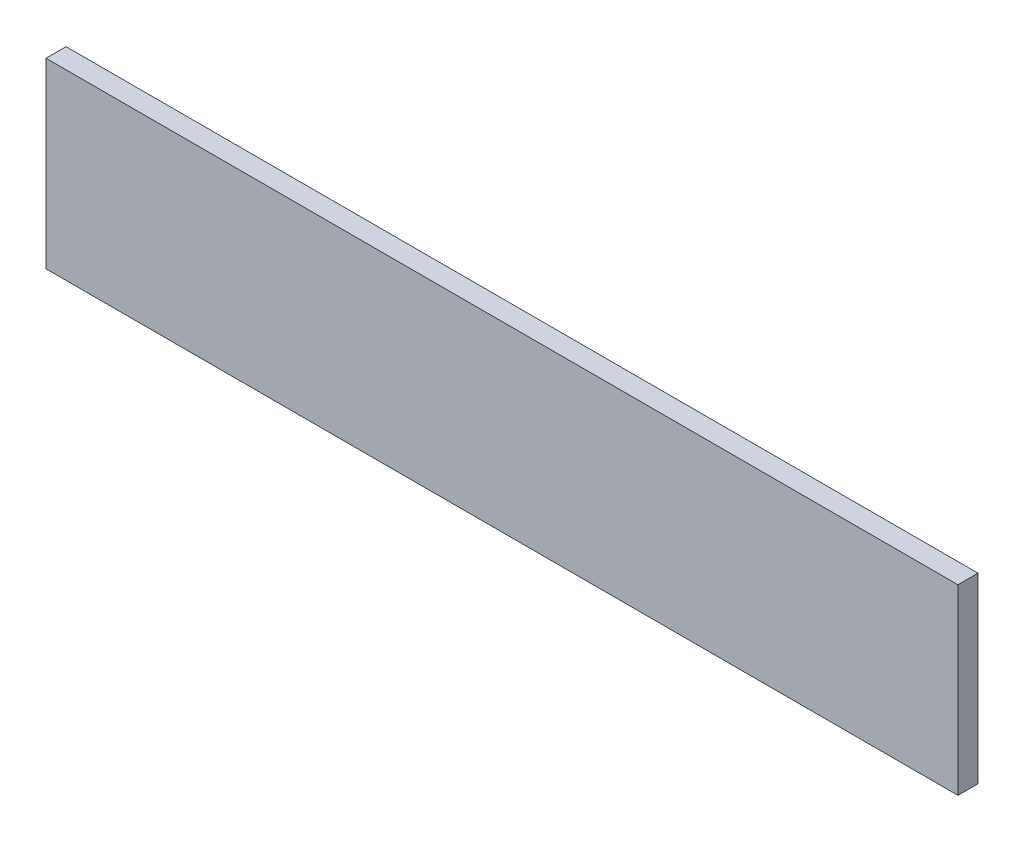
SolidWorks part; units mm, degrees
ref_plane "Front Plane" through (0, 0, 0) normal (0, 0, 1) x (1, 0, 0)
ref_plane "Top Plane" through (0, 0, 0) normal (0, 1, 0) x (1, 0, 0)
ref_plane "Right Plane" through (0, 0, 0) normal (1, 0, 0) x (0, 0, -1)
ref_plane "Plane1"
sketch "Sketch1" plane through (0, 0, 0) normal (0, 0, 1) x (1, 0, 0)
  line L0 (-500, -100) -> (500, -100)
  line L1 (500, -100) -> (500, 100)
  line L2 (500, 100) -> (-500, 100)
  line L3 (-500, 100) -> (-500, -100)
  dimension "D1" = 1000
  dimension "D2" = 200
extrude "Extrusion1" add sketch "Sketch1" along normal blind 22
